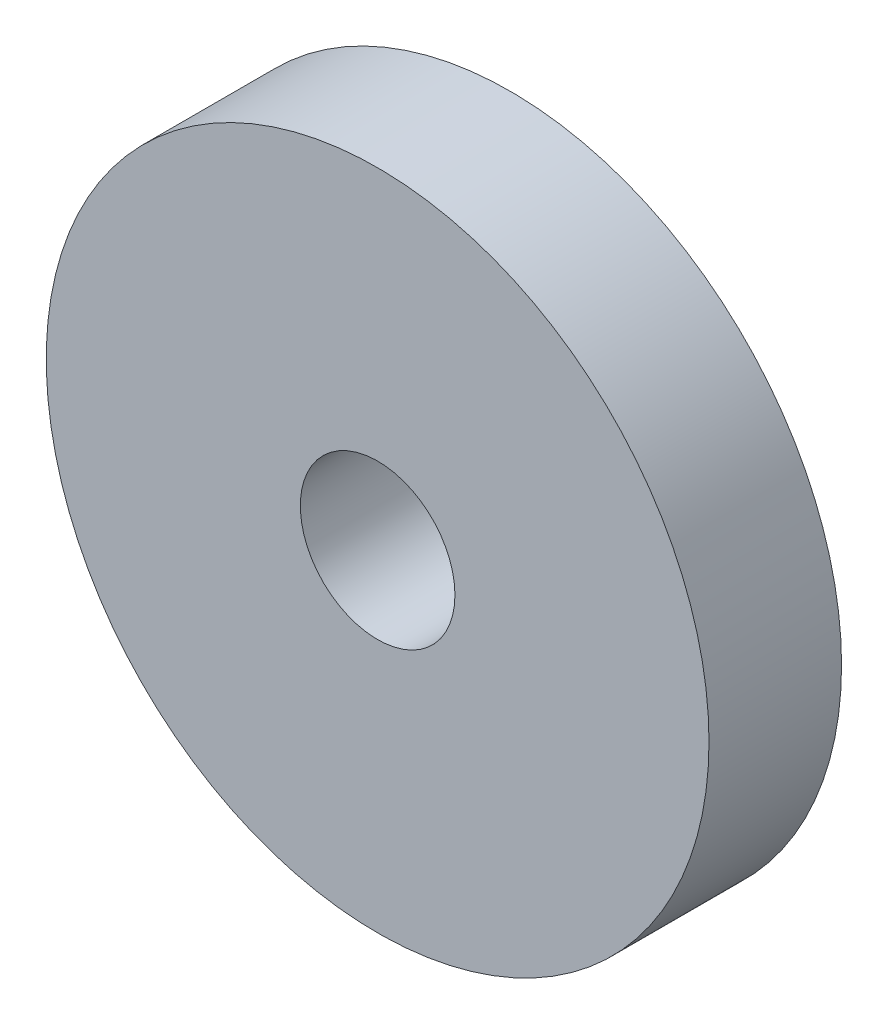
SolidWorks part; units mm, degrees
ref_plane "Front Plane" through (0, 0, 0) normal (0, 0, 1) x (1, 0, 0)
ref_plane "Top Plane" through (0, 0, 0) normal (0, 1, 0) x (1, 0, 0)
ref_plane "Right Plane" through (0, 0, 0) normal (1, 0, 0) x (0, 0, -1)
sketch "Sketch1" plane through (0, 0, 0) normal (0, 0, 1) x (1, 0, 0)
  circle A2 centre (-39.8763, 0) radius 1.75 construction
  circle A3 centre (-39.8763, 0) radius 1.75
  circle A4 centre (-39.8763, 0) radius 7.5
  dimension "D1" = 15
extrude "Boss-Extrude1" add sketch "Sketch1" along normal blind 3
